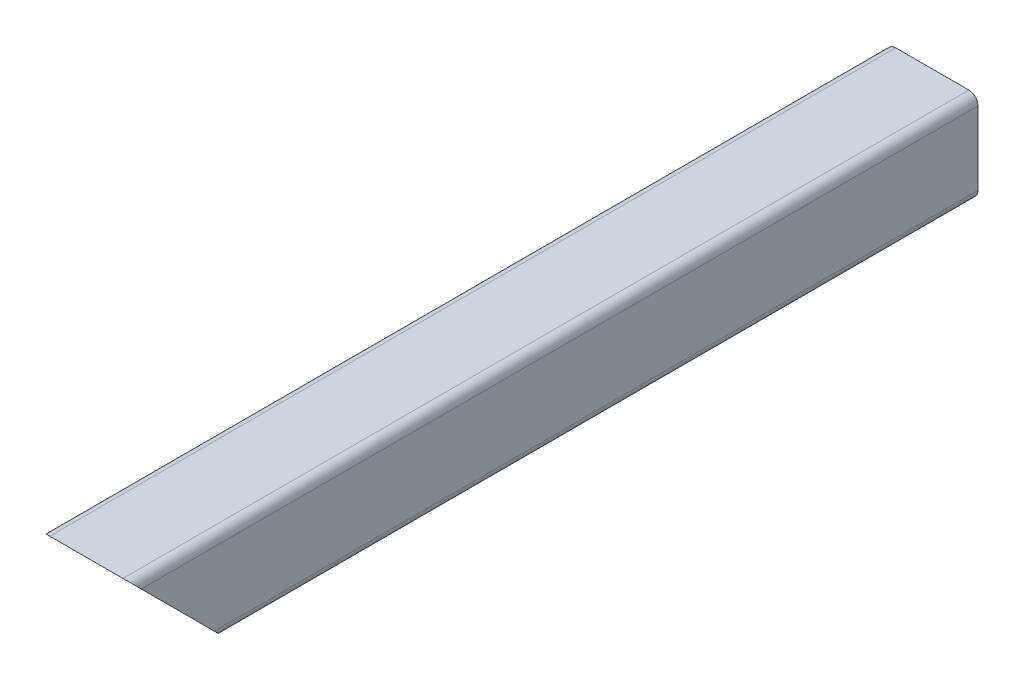
SolidWorks part; units mm, degrees
material "1.4305 (X8CrNiS18-9)"
ref_plane "Ön Düzlem" through (0, 0, 0) normal (0, 0, 1) x (1, 0, 0)
ref_plane "Üst Düzlem" through (0, 0, 0) normal (0, 1, 0) x (1, 0, 0)
ref_plane "Sağ Düzlem" through (0, 0, 0) normal (1, 0, 0) x (0, 0, -1)
sketch "Çizim1" plane through (0, 0, 0) normal (0, 0, 1) x (1, 0, 0)
  line L0 (-18, 16) -> (-18, -16)
  line L1 (-16, 20) -> (16, 20)
  line L2 (-20, 16) -> (-20, -16)
  line L3 (-16, -20) -> (16, -20)
  line L4 (20, 16) -> (20, -16)
  line L5 (-20, 20) -> (20, -20) construction
  line L6 (-20, -20) -> (20, 20) construction
  line L7 (-16, -18) -> (16, -18)
  line L8 (18, 16) -> (18, -16)
  line L9 (-16, 18) -> (16, 18)
  arc A0 (20, -16) -> (16, -20) centre (16, -16) cw
  arc A1 (16, 20) -> (20, 16) centre (16, 16) cw
  arc A2 (-16, 20) -> (-20, 16) centre (-16, 16) ccw
  arc A3 (-20, -16) -> (-16, -20) centre (-16, -16) ccw
  arc A4 (-18, -16) -> (-16, -18) centre (-16, -16) ccw
  arc A5 (18, -16) -> (16, -18) centre (16, -16) cw
  arc A6 (16, 18) -> (18, 16) centre (16, 16) cw
  arc A7 (-16, 18) -> (-18, 16) centre (-16, 16) ccw
  point P0 (0, 0)
  dimension "D3" = 4
  dimension "D1" = 40
  dimension "D2" = 40
  dimension "D4" = 2
extrude "Yükseklik-Ekstrüzyon1" add sketch "Çizim1" along normal blind 370
sketch "Çizim2" plane through (0, 0, 0) normal (0, 0, -1) x (-1, 0, 0)
  line L0 (-18.8284, 18.8284) -> (18.8284, -18.8284) construction
  arc A0 (-16, 20) -> (-20, 16) centre (-16, 16) ccw construction
  arc A1 (16, -20) -> (20, -16) centre (16, -16) ccw construction
sketch "Çizim3" plane through (0, 0, 0) normal (1, 0, 0) x (0, 0, -1)
  line L0 (-370, 20) -> (-330, -20)
  line L1 (-370, -20) -> (0, -20) construction
  line L2 (-330, -20) -> (-370, -20)
  line L3 (-370, -20) -> (-370, 20)
  dimension "D1" = 45
extrude "Kes-Ekstrüzyon1" cut sketch "Çizim3" against normal blind 43 and the other way blind 41
